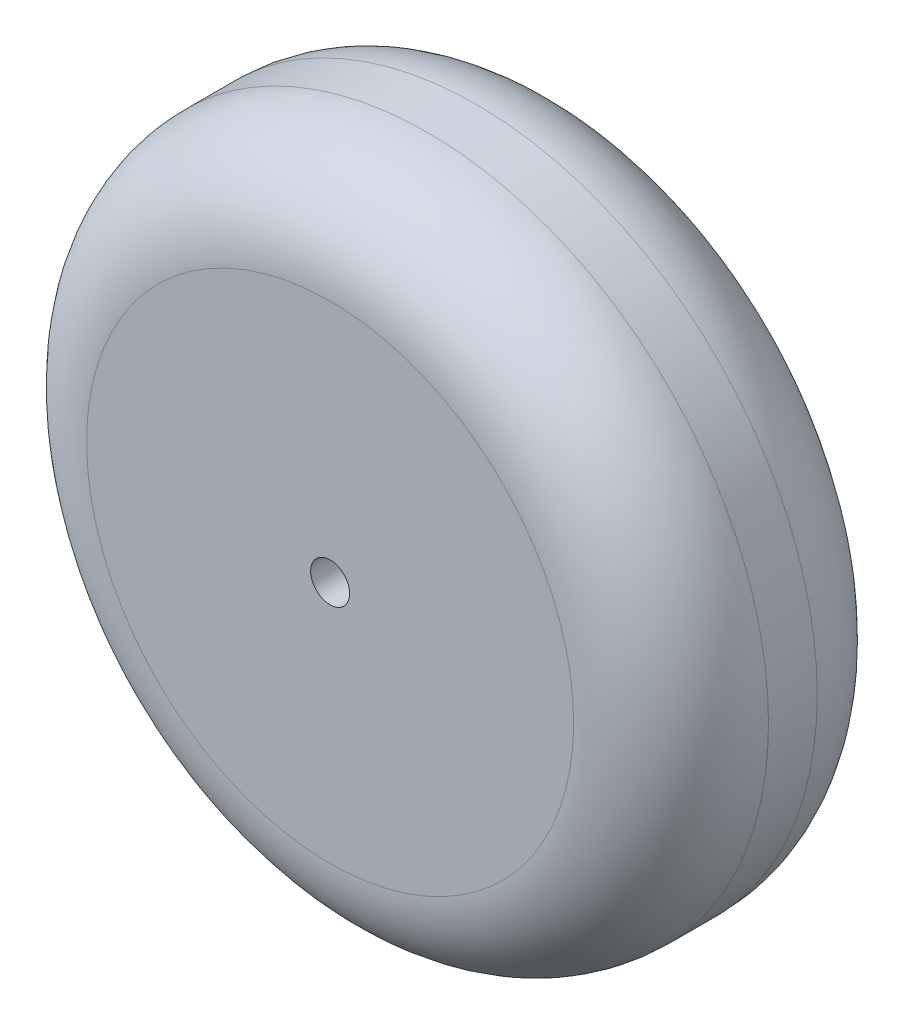
SolidWorks part; units mm, degrees
material "PA Tip 6"
ref_plane "Ön Düzlem" through (0, 0, 0) normal (0, 0, 1) x (1, 0, 0)
ref_plane "Üst Düzlem" through (0, 0, 0) normal (0, 1, 0) x (1, 0, 0)
ref_plane "Sağ Düzlem" through (0, 0, 0) normal (1, 0, 0) x (0, 0, -1)
sketch "Çizim1" plane through (0, 0, 0) normal (0, 0, 1) x (1, 0, 0)
  circle A0 centre (0, 0) radius 35
  dimension "D1" = 70
extrude "Yükseklik-Ekstrüzyon1" add sketch "Çizim1" along normal blind 25
sketch "Çizim2" plane through (0, 0, 25) normal (0, 0, 1) x (1, 0, 0)
  circle A0 centre (0, 0) radius 2
  dimension "D1" = 4
extrude "Kes-Ekstrüzyon1" cut sketch "Çizim2" against normal blind 9
fillet "Radyus1" radius 10 1 edges at (35, 0, 0)
fillet "Radyus2" radius 10 1 edges at (35, 0, 25)
